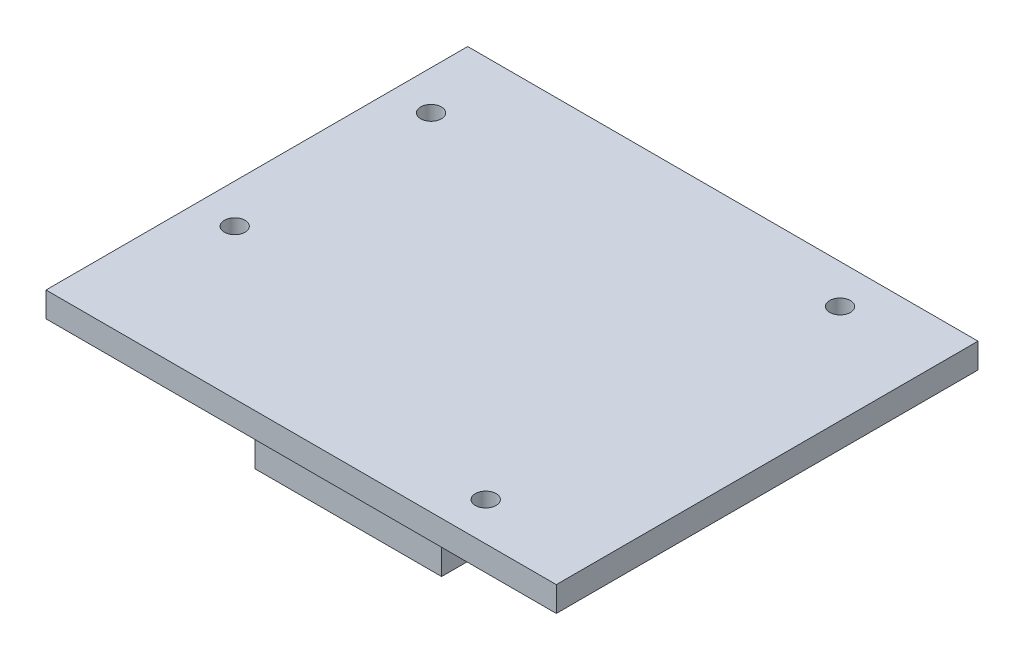
SolidWorks part; units mm, degrees
ref_plane "前基準面" through (0, 0, 0) normal (0, 0, 1) x (1, 0, 0)
ref_plane "上基準面" through (0, 0, 0) normal (0, 1, 0) x (1, 0, 0)
ref_plane "右基準面" through (0, 0, 0) normal (1, 0, 0) x (0, 0, -1)
sketch "草圖1" plane through (0, 0, 0) normal (0, 1, 0) x (1, 0, 0)
  line L0 (35.7, -24.6262) -> (22.6, -24.6262) construction
  line L1 (35.7, -29.5) -> (-35.7, -29.5)
  line L2 (35.7, -29.5) -> (35.7, 29.5)
  line L3 (35.7, 29.5) -> (-35.7, 29.5)
  line L4 (-35.7, -29.5) -> (-35.7, 29.5)
  line L5 (0, 29.5) -> (0, -29.5) construction
  line L6 (35.7, 0) -> (-35.7, 0) construction
  line L7 (17.7096, -29.5) -> (17.7096, -25.97) construction
  point P0 (0, 0)
  dimension "D1" = 59
  dimension "D2" = 71.4
extrude "填料-伸長1" add sketch "草圖1" against normal blind 3.5
sketch "草圖2" plane through (0, 0, 0) normal (0, 1, 0) x (1, 0, 0)
  line L0 (35.7, -24.1305) -> (22, -24.1305) construction
  line L1 (35.7, -29.5) -> (35.7, 29.5) construction
  line L2 (20.4534, -29.5) -> (20.4534, -25.6) construction
  line L3 (-35.7, -29.5) -> (35.7, -29.5) construction
  line L4 (-30.2236, 29.5) -> (-30.2236, 20.3) construction
  line L5 (-30.3149, -29.5) -> (-30.3149, -10) construction
  line L6 (35.7, 29.5) -> (-35.7, 29.5) construction
  line L7 (-35.7, -8.578) -> (-31.7, -8.578) construction
  line L8 (-35.7, 29.5) -> (-35.7, -29.5) construction
  line L9 (-35.7, -29.5) -> (35.7, -29.5) construction
  line L10 (35.7, 24.1305) -> (23.2, 24.1305) construction
  line L11 (35.7, -29.5) -> (35.7, 29.5) construction
  line L12 (21.9144, 29.5) -> (21.9144, 25.44) construction
  circle A0 centre (20.4534, -24.1305) radius 1.45
  circle A1 centre (-30.2236, 18.9) radius 1.45
  circle A2 centre (-30.2236, -8.578) radius 1.45
  circle A3 centre (21.85, 24.05) radius 1.45
  point P30 (21.2752, 25.5668)
  point P31 (20.3621, 25.7494)
  point P32 (18.9011, 24.5624)
  point P33 (21.0013, 28)
  point P34 (22, 25.7494)
  point P35 (21.9144, 28)
  point P36 (0, 0)
  point P37 (0, 0)
  point P38 (0, 0)
  point P39 (0, 0)
  point P40 (0, 0)
  point P41 (0, 0)
  point P42 (0, 0)
  point P43 (21.9144, 23.1685)
  point P44 (21.9144, 24.0504)
  point P45 (21.9144, 24.1305)
  point P46 (20.4534, -24.1305)
  point P47 (21.9144, 24.1305)
  point P48 (-30.3149, -8.4978)
  point P49 (-30.3149, -8.578)
extrude "除料-伸長4" cut sketch "草圖2" along normal blind 8.5 and the other way blind 15
sketch "草圖5" plane through (0, -3.5, 0) normal (0, -1, 0) x (-1, 0, 0)
  line L1 (-13.055, 22.9) -> (13.055, 22.9)
  line L2 (-13.055, 22.9) -> (-13.055, -22.9)
  line L3 (-13.055, -22.9) -> (13.055, -22.9)
  line L4 (13.055, 22.9) -> (13.055, -22.9)
  line L5 (0, -22.9) -> (0, 22.9) construction
  line L6 (-13.055, 0) -> (13.055, 0) construction
  point P0 (0, 0)
  dimension "D1" = 26.11
  dimension "D2" = 45.8
extrude "填料-伸長2" add sketch "草圖5" along normal blind 10.15
sketch "草圖6" plane through (0, -13.65, 0) normal (0, -1, 0) x (1, 0, 0)
  line L1 (10, -19.775) -> (-10, -19.775)
  line L2 (10, -19.775) -> (10, 19.775)
  line L3 (10, 19.775) -> (-10, 19.775)
  line L4 (-10, -19.775) -> (-10, 19.775)
  line L5 (0, 19.775) -> (0, -19.775) construction
  line L6 (10, 0) -> (-10, 0) construction
  point P0 (0, 0)
  dimension "D1" = 39.55
  dimension "D2" = 20
extrude "除料-伸長5" cut sketch "草圖6" against normal blind 10.15
